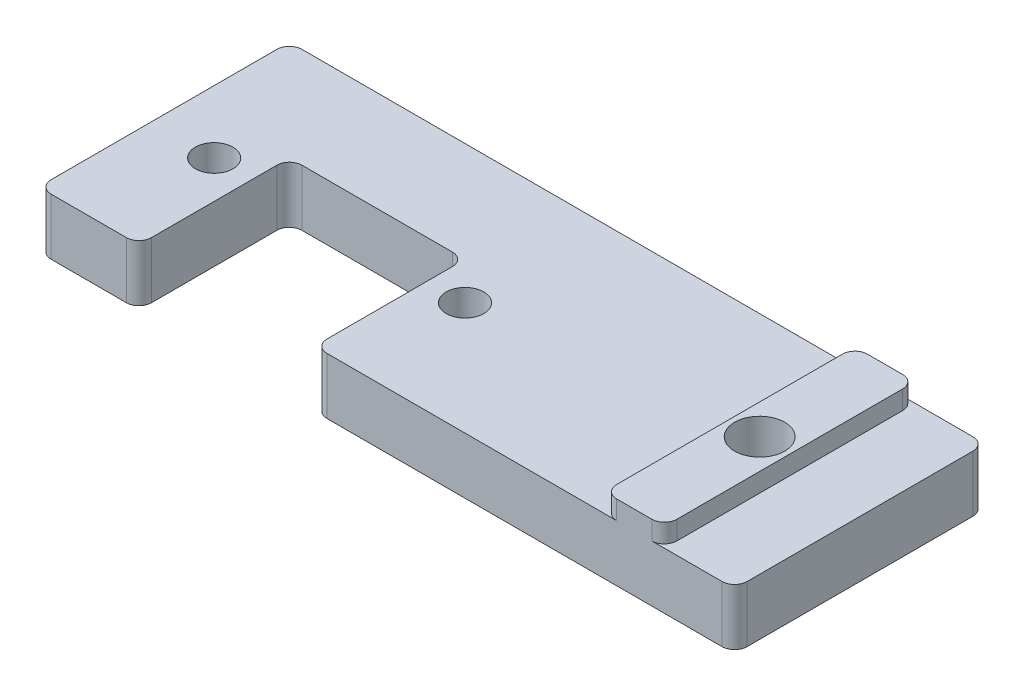
SolidWorks part; units mm, degrees
material "ABS"
ref_plane "Plan de face" through (0, 0, 0) normal (0, 0, 1) x (1, 0, 0)
ref_plane "Plan de dessus" through (0, 0, 0) normal (0, 1, 0) x (1, 0, 0)
ref_plane "Plan de droite" through (0, 0, 0) normal (1, 0, 0) x (0, 0, -1)
sketch "Esquisse1" plane through (0, 0, 0) normal (0, 1, 0) x (1, 0, 0)
  line L1 (7, -9) -> (15, -9)
  line L2 (7, -9) -> (7, 3)
  line L4 (15, -9) -> (15, 11)
  line L5 (15, 11) -> (0, 11)
  line L7 (7, 3) -> (0, 3)
  line L8 (0, 11) -> (0, 3)
  circle A0 centre (10, 0) radius 1.5
  dimension "D1" = 10
  dimension "D2" = 3
  dimension "D4" = 9
  dimension "D3" = 15
  dimension "D5" = 7
  dimension "D6" = 3
  dimension "D7" = 11
extrude "Boss.-Extru.1" add sketch "Esquisse1" along normal blind 4.5
fillet "Congé1" radius 1 4 edges at (15, 2.25, -11) (15, 2.25, 9) (7, 2.25, 9) (7, 2.25, -3)
mirror "Symétrie1" about plane through (0, 4.5, -11) normal (1, 0, 0) of bodies 101 102
sketch "Esquisse2" plane through (0, 4.5, 0) normal (0, 1, 0) x (1, 0, 0)
  line L0 (8, -9) -> (14, -9) construction
  line L1 (14, 11) -> (40.5, 11)
  line L2 (14, 11) -> (14, -9)
  line L3 (14, -9) -> (40.5, -9)
  line L4 (40.5, 11) -> (40.5, -9)
  dimension "D1" = 40.5
extrude "Boss.-Extru.2" add sketch "Esquisse2" against normal up to surface (4.5 mm away) up to face at (0, 0, 1)
sketch "Esquisse3" plane through (0, 4.5, 0) normal (0, -1, 0) x (1, 0, 0)
  line L0 (8, 9) -> (40.5, 9) construction
  line L1 (30.1, 9) -> (34.9, 9)
  line L2 (30.1, 9) -> (30.1, -11)
  line L3 (30.1, -11) -> (34.9, -11)
  line L4 (34.9, 9) -> (34.9, -11)
  line L5 (40.5, -11) -> (-14, -11) construction
  line L6 (32.5, 9) -> (32.5, -1) construction
  line L7 (32.5, -1) -> (34.9, -1) construction
  line L8 (40.5, -11) -> (40.5, 9) construction
  circle A0 centre (32.5, -1) radius 2
  dimension "D1" = 4.8
  dimension "D2" = 4
  dimension "D3" = 8
  dimension "D4" = 5.6
extrude "Boss.-Extru.3" add sketch "Esquisse3" against normal blind 1.5
sketch "Esquisse4" plane through (0, 4.5, 0) normal (0, -1, 0) x (1, 0, 0)
  circle A1 centre (32.5, -1) radius 2
  circle A2 centre (32.5, -1) radius 2
  dimension "D1" = 0
extrude "Enlèv. mat.-Extru.1" cut sketch "Esquisse4" along normal through all
fillet "Congé2" radius 1 6 edges at (40.5, 2.25, -11) (40.5, 2.25, 9)
sketch "Esquisse5" plane through (0, 4.5, 0) normal (0, 1, 0) x (1, 0, 0)
  line L0 (-15, -8) -> (-15, 10) construction
  line L1 (-15, 8.5) -> (22.3, 8.5)
  line L2 (-15, 8.5) -> (-15, 5.5)
  line L3 (-15, 5.5) -> (22.3, 5.5)
  line L4 (22.3, 8.5) -> (22.3, 5.5)
  line L5 (31.1, 11) -> (-14, 11) construction
  line L6 (-6, 3) -> (6, 3) construction
  circle A0 centre (32.5, 1) radius 2 construction
  dimension "D1" = 3
  dimension "D2" = 2.5
  dimension "D3" = 2.5
  dimension "D4" = 10.2
extrude "Boss.-Extru.4" [suppressed] add sketch "Esquisse5" along normal blind 3
fillet "Congé3" [suppressed] radius 1
